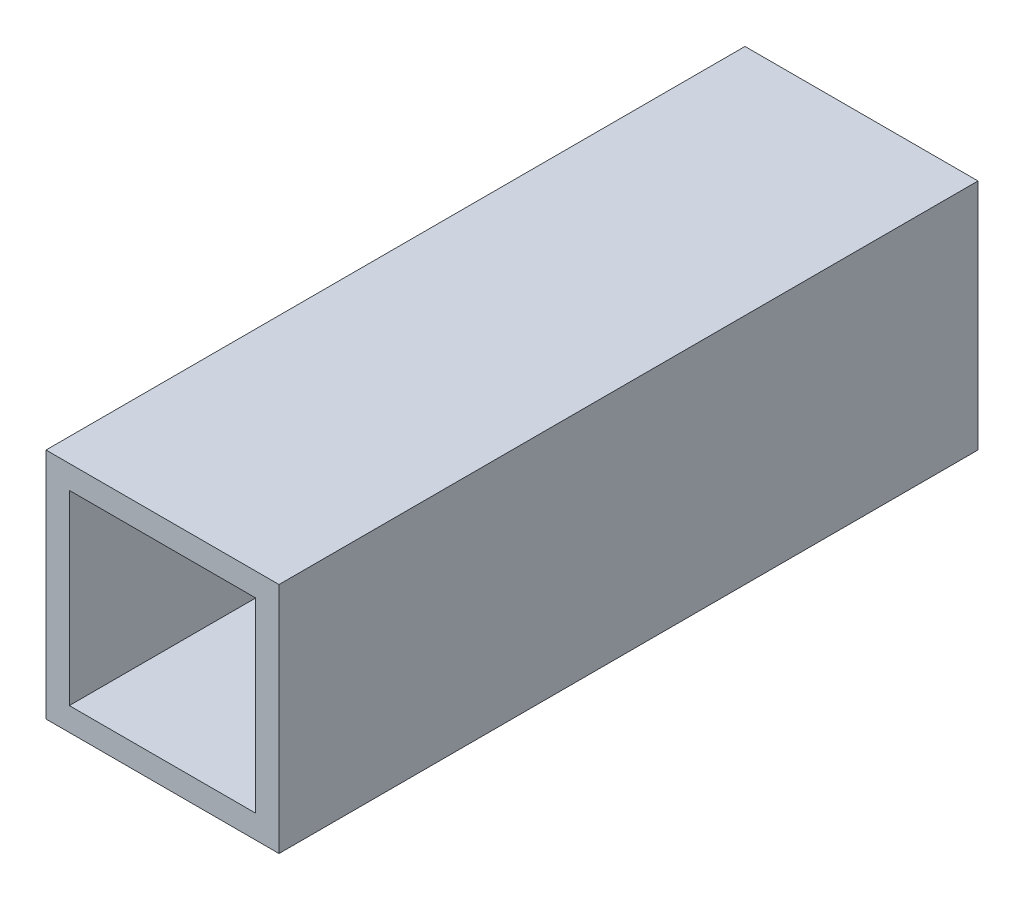
SolidWorks part; units mm, degrees
ref_plane "Front Plane" through (0, 0, 0) normal (0, 0, 1) x (1, 0, 0)
ref_plane "Top Plane" through (0, 0, 0) normal (0, 1, 0) x (1, 0, 0)
ref_plane "Right Plane" through (0, 0, 0) normal (1, 0, 0) x (0, 0, -1)
sketch "Sketch2" plane through (0, 0, 0) normal (0, 0, -1) x (1, 0, 0)
  line L0 (-20, -20) -> (-20, 20)
  line L1 (-25, -25) -> (25, -25)
  line L2 (-25, -25) -> (-25, 25)
  line L3 (-25, 25) -> (25, 25)
  line L4 (25, -25) -> (25, 25)
  line L5 (-20, 20) -> (20, 20)
  line L6 (20, -20) -> (20, 20)
  line L7 (-20, -20) -> (20, -20)
  dimension "tube_width" = 50
  dimension "tube_height" = 50
  dimension "D1" = 25
  dimension "D3" = 25
  dimension "D2" = 5
extrude "Boss-Extrude1" add sketch "Sketch2" against normal blind 150
equation "\"D1@Sketch2\"=\"tube_width@Sketch2\"/2"
equation "\"D3@Sketch2\"=\"tube_height@Sketch2\"/2"
